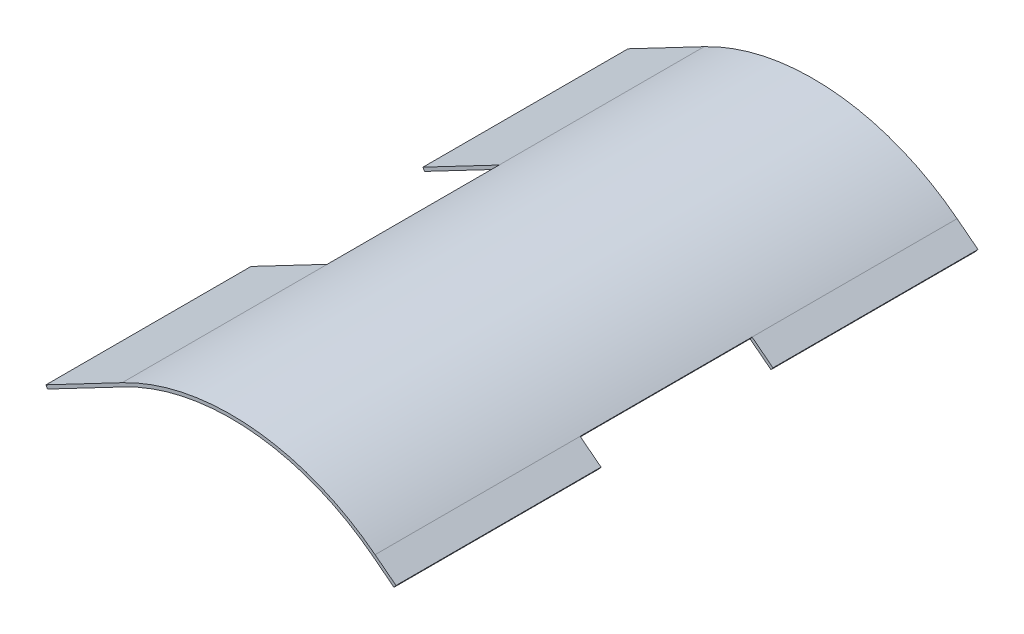
SolidWorks part; units mm, degrees
ref_plane "Front Plane" through (0, 0, 0) normal (0, 0, 1) x (1, 0, 0)
ref_plane "Top Plane" through (0, 0, 0) normal (0, 1, 0) x (1, 0, 0)
ref_plane "Right Plane" through (0, 0, 0) normal (1, 0, 0) x (0, 0, -1)
sketch "Sketch1" plane through (0, 0, 0) normal (0, 0, 1) x (1, 0, 0)
  line L0 (-58.7481, 196.3413) -> (-70.2624, 190.3063)
  line L1 (-21.0384, 192.9891) -> (-17.8786, 190.5363)
  arc A0 (-21.0384, 192.9891) -> (-58.7481, 196.3413) centre (-42.5, 165.3413) ccw construction
  arc A1 (-21.0384, 192.9891) -> (-58.7481, 196.3413) centre (-42.5, 165.3413) ccw construction
  arc A2 (-21.0384, 192.9891) -> (-58.7481, 196.3413) centre (-42.5, 165.3413) ccw
extrude "Extrude-Thin1" add sketch "Sketch1" along normal mid plane 88 thin
sketch "Sketch2" plane through (-93.6237, 178.6264, 0) normal (-0.4642, 0.8857, 0) x (0, 0, 1)
  line L0 (44, 26.1137) -> (-44, 26.1137) construction
  line L1 (-13, 26.1137) -> (13, 26.1137)
  line L2 (-13, 26.1137) -> (-13, 39.1137)
  line L3 (-13, 39.1137) -> (13, 39.1137)
  line L4 (13, 26.1137) -> (13, 39.1137)
  line L5 (44, 39.1137) -> (-44, 39.1137) construction
  line L7 (0, -22.6051) -> (0, 107.3983) construction
extrude "Cut-Extrude1" cut sketch "Sketch2" against normal up to next
sketch "Sketch3" plane through (85.8762, 110.6295, 0) normal (0.6132, 0.7899, 0) x (0.7899, -0.6132, 0)
  line L0 (-134.9578, -44) -> (-134.9578, 44) construction
  line L1 (-134.9578, 13) -> (-130.9578, 13)
  line L2 (-134.9578, 13) -> (-134.9578, -13)
  line L3 (-134.9578, -13) -> (-130.9578, -13)
  line L4 (-130.9578, 13) -> (-130.9578, -13)
  line L5 (-130.9578, -44) -> (-130.9578, 44) construction
  line L6 (-167.2565, 13) -> (-172.6514, 13) construction
  line L7 (-172.6514, -13) -> (-167.2565, -13) construction
extrude "Cut-Extrude2" cut sketch "Sketch3" against normal up to next
